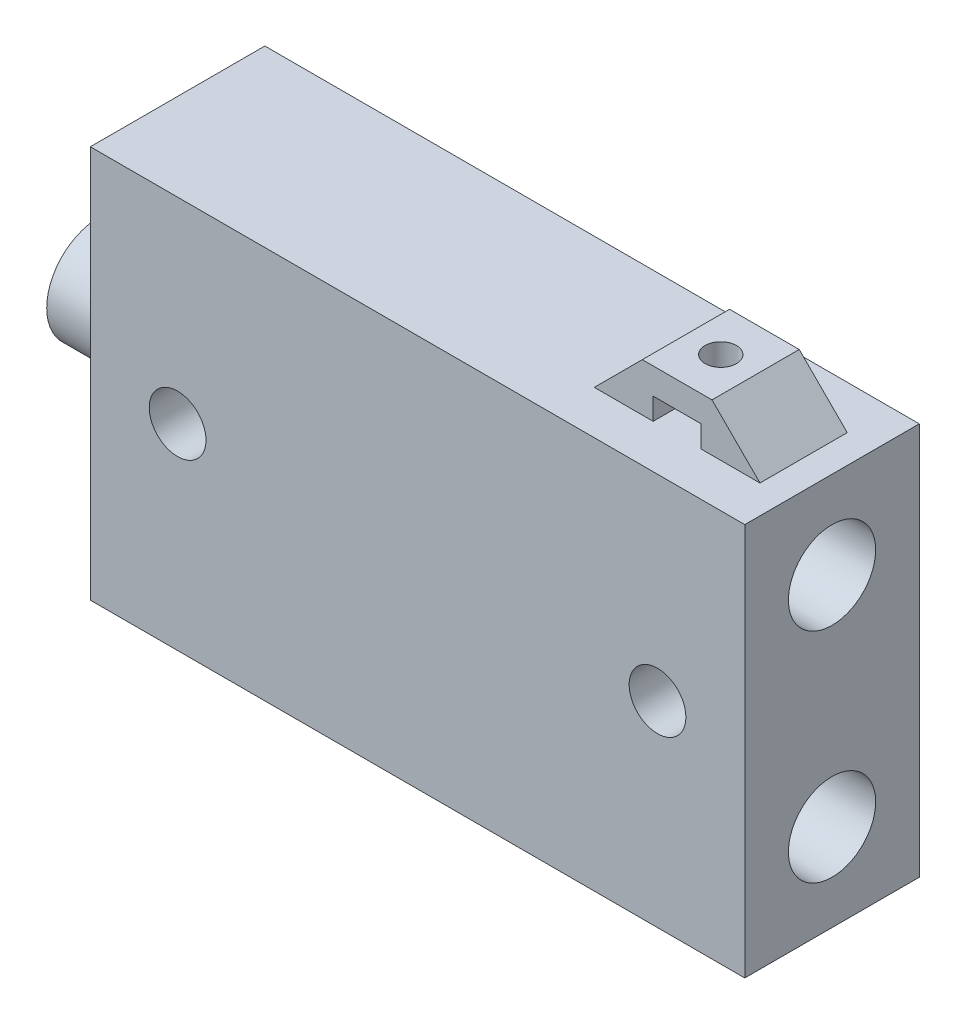
SolidWorks part; units mm, degrees
ref_plane "Front Plane" through (0, 0, 0) normal (0, 0, 1) x (1, 0, 0)
ref_plane "Top Plane" through (0, 0, 0) normal (0, 1, 0) x (1, 0, 0)
ref_plane "Right Plane" through (0, 0, 0) normal (1, 0, 0) x (0, 0, -1)
sketch "Sketch1" plane through (0, 0, 0) normal (1, 0, 0) x (0, 0, -1)
  line L0 (10, 0) -> (10, 10) construction
  line L1 (0, 0) -> (20, 0)
  line L2 (0, 0) -> (0, 45)
  line L3 (0, 45) -> (20, 45)
  line L4 (20, 0) -> (20, 45)
  line L5 (10, 10) -> (10, 35) construction
  line L6 (10, 35) -> (10, 45) construction
  circle A0 centre (10, 35) radius 5
  circle A1 centre (10, 10) radius 5
  dimension "D1" = 10
  dimension "D2" = 45
  dimension "D4" = 5
  dimension "D3" = 25
  dimension "D5" = 20
  dimension "D6" = 5
extrude "Boss-Extrude1" add sketch "Sketch1" along normal blind 75
sketch "Sketch2" plane through (0, 0, 0) normal (0, 0, 1) x (1, 0, 0)
  line L0 (0, 22.5) -> (10, 22.5) construction
  line L1 (0, 45) -> (0, 0) construction
  line L2 (10, 22.5) -> (65, 22.5) construction
  line L3 (65, 22.5) -> (75, 22.5) construction
  line L4 (75, 45) -> (75, 0) construction
  circle A0 centre (10, 22.5) radius 3.25
  circle A1 centre (65, 22.5) radius 3.25
  dimension "D1" = 6.5
  dimension "D2" = 10
extrude "Cut-Extrude1" cut sketch "Sketch2" against normal through all
ref_plane "Plane1" through (0, 0, -10) normal (0, 0, 1) x (1, 0, 0)
sketch "Sketch4" plane through (0, 0, -10) normal (0, 0, 1) x (1, 0, 0)
  line L2 (0, 40) -> (75, 40)
  line L3 (75, 30) -> (0, 30)
  line L4 (75, 30) -> (0, 30) construction
  line L5 (0, 40) -> (75, 40) construction
  line L6 (12, 40) -> (13.7321, 41)
  line L7 (13.7321, 41) -> (61.2679, 41)
  line L8 (61.2679, 41) -> (63, 40)
  line L9 (63, 40) -> (12, 40)
  line L10 (75, 45) -> (0, 45) construction
  line L11 (37.5, 45) -> (37.5, 41) construction
  line L12 (0, 45) -> (0, 0) construction
  dimension "D1" = 1
  dimension "D2" = 30
  dimension "D3" = 12
revolve "Cut-Revolve1" cut sketch "Sketch4" angle 360 about axis through (75, 35, -10) along (-1, 0, 0)
ref_plane "Plane2" through (0, 22.5, 0) normal (0, 1, 0) x (1, 0, 0)
mirror "Mirror1" about plane through (0, 22.5, 0) normal (0, 1, 0) of "Cut-Revolve1"
sketch "Sketch5" plane through (0, 0, 0) normal (-1, 0, 0) x (0, 0, 1)
  line L0 (-10, 35) -> (-10, 10) construction
  circle A0 centre (-10, 22.5) radius 6
  circle A1 centre (-10, 22.5) radius 2.75
  dimension "D1" = 5.5
  dimension "D2" = 12
extrude "Boss-Extrude3" add sketch "Sketch5" along normal blind 9
sketch "Sketch6" plane through (0, 0, 0) normal (-1, 0, 0) x (0, 0, 1)
  circle A1 centre (-10, 22.5) radius 2.75
  circle A2 centre (-10, 22.5) radius 2.75
  dimension "D1" = 0
extrude "Cut-Extrude2" cut sketch "Sketch6" against normal up to next
sketch "Sketch8" plane through (0, 0, -10) normal (0, 0, 1) x (1, 0, 0)
  line L0 (52.7574, 45) -> (58.2574, 50.5)
  line L1 (75, 45) -> (0, 45) construction
  line L2 (58.2574, 50.5) -> (66.2426, 50.5)
  line L3 (66.2426, 50.5) -> (71.7426, 45)
  line L4 (71.7426, 45) -> (65, 45)
  line L5 (62.25, 50.5) -> (62.25, 47.5) construction
  line L6 (59.5, 45) -> (59.5, 47.5)
  line L7 (59.5, 47.5) -> (65, 47.5)
  line L8 (65, 47.5) -> (65, 45)
  line L9 (59.5, 45) -> (52.7574, 45)
  line L10 (75, 45) -> (75, 0) construction
  point P10 (62.25, 47.5)
  dimension "D1" = 2.5
  dimension "D2" = 5.5
  dimension "D3" = 3
  dimension "D4" = 3
  dimension "D5" = 10
extrude "Boss-Extrude4" add sketch "Sketch8" along normal mid plane 10
sketch "Sketch9" plane through (0, 50.5, 0) normal (0, 1, 0) x (1, 0, 0)
  line L0 (-24.75, 10) -> (24.75, 10) construction
  line L1 (66.2426, 15) -> (58.2574, 15) construction
  circle A0 centre (62.25, 10) radius 1.8
  point P6 (62.25, 15)
  dimension "D1" = 3.6
extrude "Cut-Extrude3" cut sketch "Sketch9" against normal up to surface (9.7764 mm away)
